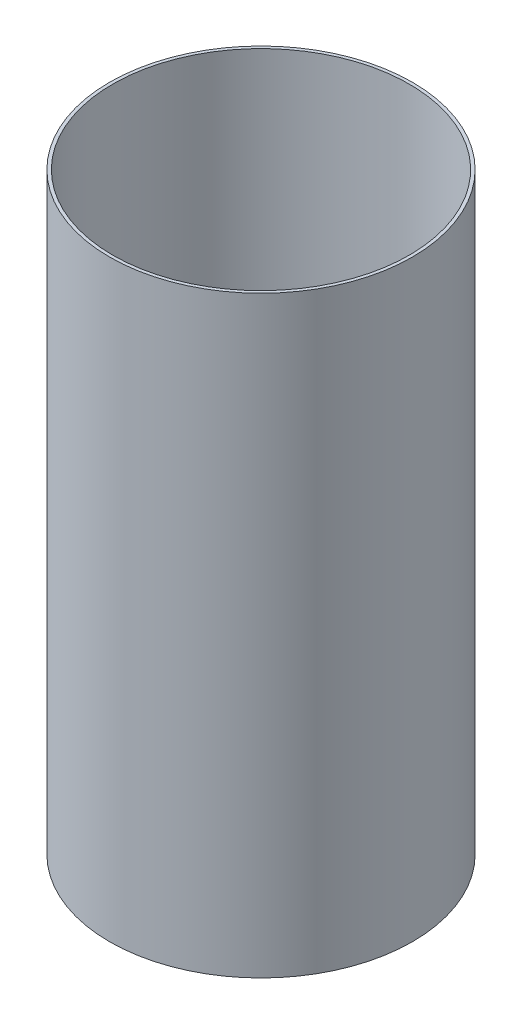
SolidWorks part; units mm, degrees
ref_plane "Front Plane" through (0, 0, 0) normal (0, 0, 1) x (1, 0, 0)
ref_plane "Top Plane" through (0, 0, 0) normal (0, 1, 0) x (1, 0, 0)
ref_plane "Right Plane" through (0, 0, 0) normal (1, 0, 0) x (0, 0, -1)
sketch "Sketch1" plane through (0, 0, 0) normal (0, 1, 0) x (1, 0, 0)
  circle A0 centre (0, 0) radius 74.6125
  circle A1 centre (0, 0) radius 76.2
  dimension "D1" = 152.4
  dimension "D2" = 1.5875
extrude "Boss-Extrude1" add sketch "Sketch1" along normal mid plane 298.45
